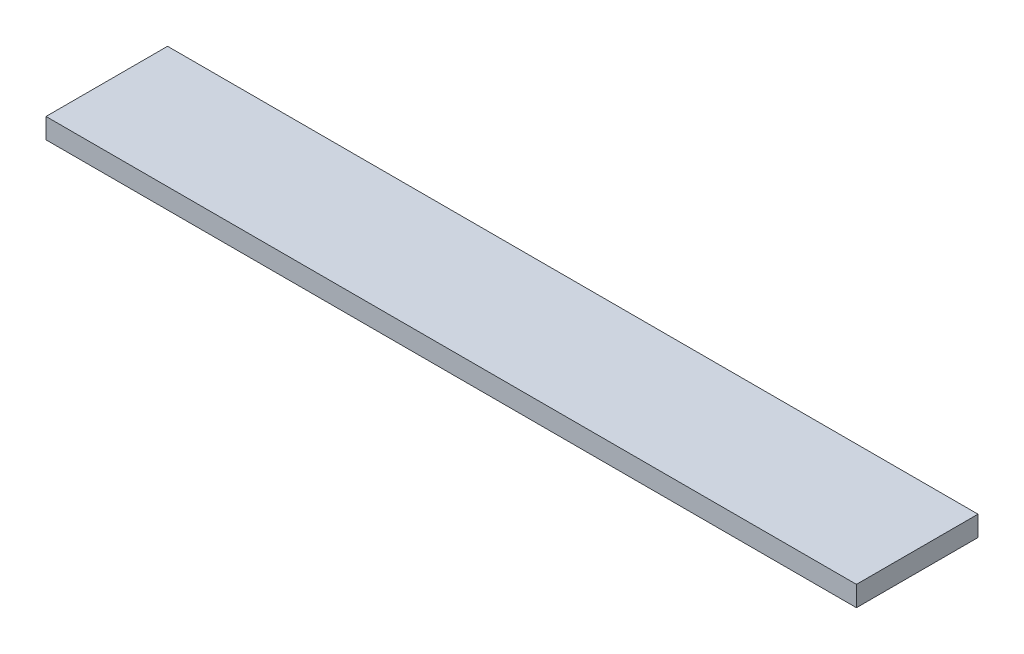
SolidWorks part; units mm, degrees
ref_plane "Front Plane" through (0, 0, 0) normal (0, 0, 1) x (1, 0, 0)
ref_plane "Top Plane" through (0, 0, 0) normal (0, 1, 0) x (1, 0, 0)
ref_plane "Right Plane" through (0, 0, 0) normal (1, 0, 0) x (0, 0, -1)
sketch "Sketch1" plane through (0, 0, 0) normal (1, 0, 0) x (0, 0, -1)
  line L1 (-76.2, -12.7) -> (76.2, -12.7)
  line L2 (-76.2, -12.7) -> (-76.2, 12.7)
  line L3 (-76.2, 12.7) -> (76.2, 12.7)
  line L4 (76.2, -12.7) -> (76.2, 12.7)
  line L5 (-76.2, -12.7) -> (76.2, 12.7) construction
  line L6 (-76.2, 12.7) -> (76.2, -12.7) construction
  point P0 (0, 0)
  dimension "D1" = 152.4
  dimension "D2" = 25.4
extrude "Boss-Extrude1" add sketch "Sketch1" along normal blind 1016
